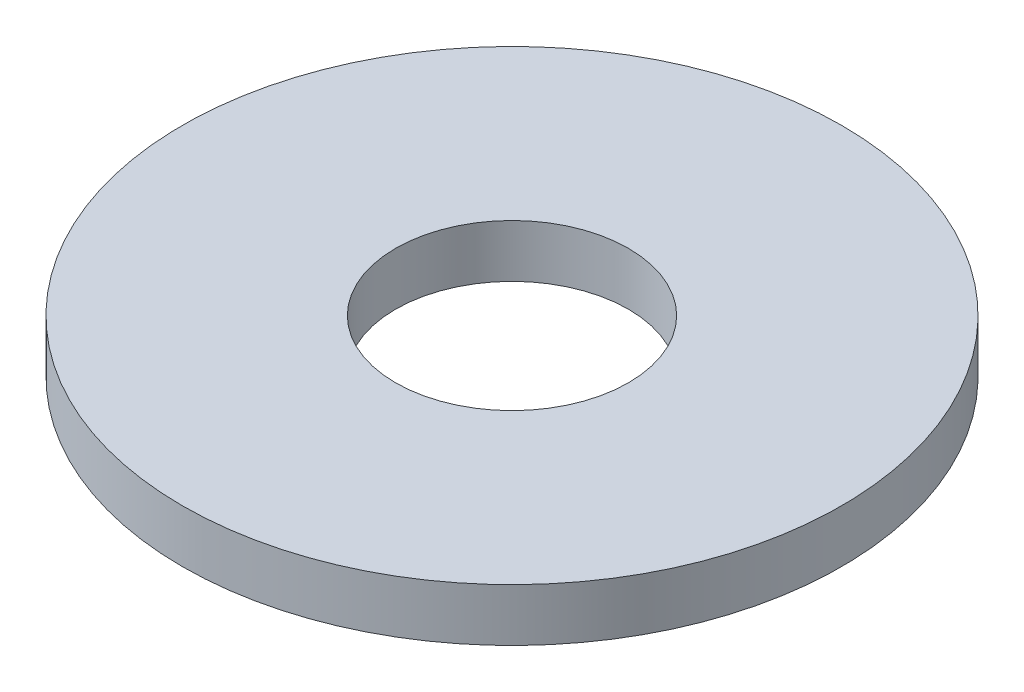
SolidWorks part; units mm, degrees
ref_plane "Front Plane" through (0, 0, 0) normal (0, 0, 1) x (1, 0, 0)
ref_plane "Top Plane" through (0, 0, 0) normal (0, 1, 0) x (1, 0, 0)
ref_plane "Right Plane" through (0, 0, 0) normal (1, 0, 0) x (0, 0, -1)
sketch "Sketch1" plane through (0, 0, 0) normal (0, 1, 0) x (1, 0, 0)
  circle A0 centre (0, 0) radius 2.65
  circle A1 centre (0, 0) radius 7.5
extrude "Boss-Extrude1" add sketch "Sketch1" along normal blind 1.2
